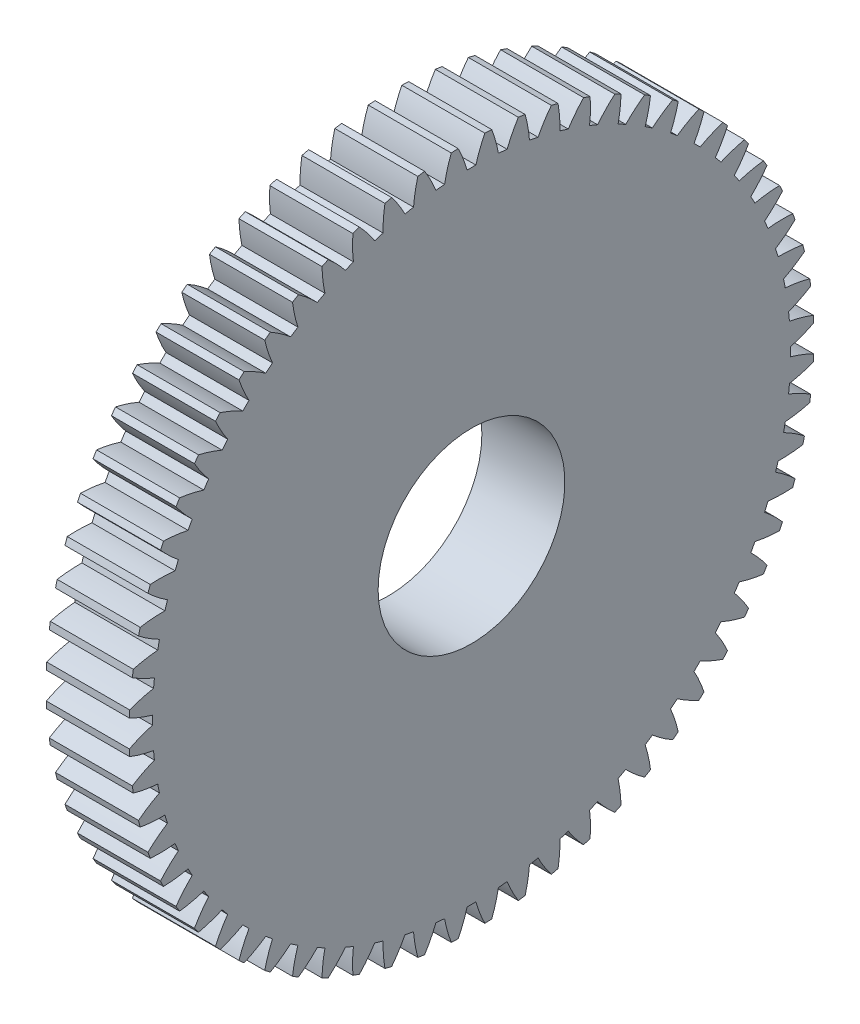
SolidWorks part; units mm, degrees
ref_plane "Plane1" through (0, 0, 0) normal (0, 0, 1) x (1, 0, 0)
ref_plane "Plane2" through (0, 0, 0) normal (0, 1, 0) x (1, 0, 0)
ref_plane "Plane3" through (0, 0, 0) normal (1, 0, 0) x (0, 0, -1)
sketch "HoldingSke" plane through (0, 0, 0) normal (0, 1, 0) x (1, 0, 0)
  line L0 (0, 0) -> (0.0877, -0.1798)
  line L1 (-15, 0) -> (100, 0) construction
  line L2 (0, 0) -> (-2.1039, 2.3779)
  line L3 (0, 0) -> (-11.863, 4.5341)
  line L4 (0, 0) -> (3.7858, 7.762)
  line L5 (0, 0) -> (-46.8476, -17.4728)
  line L6 (0, 0) -> (-33.1585, -22.3721)
  line L7 (-2.1039, 2.3779) -> (8.6586, 51.2059)
  line L8 (-76.2, 54.61) -> (-72.9, 54.61)
  line L9 (-71.009, 38.7566) -> (-53.1078, 45.2721)
  line L10 (-76.2, 71.12) -> (104.1128, 71.12)
  line L11 (0, 0) -> (-40, 0)
  line L12 (-76.2, 101.6) -> (-76.033, 101.6)
  line L13 (24.9733, 27.94) -> (52.9518, 28.4284)
  line L14 (24.9733, 27.94) -> (24.9743, 27.94)
  line L15 (24.9733, 27.94) -> (100.4006, 29.5858)
  line L16 (-63.627, -5) -> (-12.827, -5)
  circle A0 centre (0, 0) radius 20
  circle A1 centre (0, 0) radius 37.5
  circle A2 centre (0, 0) radius 37.5
  circle A3 centre (0, 0) radius 20
  dimension "MHD" = 75
  dimension "Hub_dia" = 75
  dimension "Bore" = 40
  dimension "MBD" = 40
  dimension "Num_teeth" = 64
  dimension "Pitch" = 0.2
  dimension "Overall_len" = 50
  dimension "Show_teeth" = 64
  dimension "Thickness" = 40
  dimension "OAL" = 50.0001
  dimension "T_dim" = 3.3
  dimension "Ap" = 20
  dimension "H" = 19.05
  dimension "Pitch_radius" = 180.3128
  dimension "Width" = 40
  dimension "Backlash" = 0.167
  dimension "Addendum_fac" = 1
  dimension "Dedendum_fac" = 1.25
  dimension "Clearance_fac" = 0.25
  dimension "Dedendum_add" = 0.001
  dimension "Module" = 5
sketch "BasProSke" plane through (0, 0, 0) normal (0, 1, 0) x (1, 0, 0)
  line L0 (-10, 0) -> (60, 0) construction
  line L1 (0, 0) -> (0, 165)
  line L2 (0, 0) -> (40, 0)
  line L3 (40, 0) -> (40, 165)
  line L4 (40, 165) -> (0, 165)
  dimension "Thickness" = 40
  dimension "Diameter" = 330
revolve "Base-Revolve" add sketch "BasProSke" angle 360 about L0
sketch "TooCutSke" plane through (0, 0, 0) normal (1, 0, 0) x (0, 0, -1)
  line L1 (0, 0) -> (0, 107) construction
  line L2 (0, 0) -> (-4.2188, 159.9444) construction
  line L3 (0, 0) -> (-15.6976, 319.5321) construction
  line L4 (-4.2188, 159.9444) -> (-7.8488, 159.766) construction
  arc A0 (2.1013, 153.7346) -> (-2.1013, 153.7346) centre (0, 0) ccw
  arc A1 (6.4457, 164.8995) -> (-6.4457, 164.8995) centre (0, 0) ccw
  circle A2 centre (0, 0) radius 160 construction
  circle A3 centre (0, 0) radius 150.3508 construction
  arc A4 (-2.1013, 153.7346) -> (-6.4457, 164.8995) centre (-63.6555, 136.2107) ccw
  arc A5 (6.4457, 164.8995) -> (2.1013, 153.7346) centre (63.6555, 136.2107) ccw
  dimension "Root_dia" = 307.498
  dimension "Overcut_dia" = 330.0508
  dimension "Pitch_dia" = 320
  dimension "Base_dia" = 300.7016
  dimension "Flank_rad" = 64
  dimension "Half_ang" = 2.813
  dimension "Half_CT" = 3.6343
extrude "ToothCut" cut sketch "TooCutSke" along normal through all
fillet "Breaks" [suppressed] radius 0.1
fillet "RootFillets" [suppressed] radius 1.251
pattern_circular "TeethCuts" count 64 over 360 about axis through (0, 0, 0) along (1, 0, 0) of "ToothCut", "RootFillets", "Breaks"
sketch "HubNeaOneSke" plane through (0, 0, 0) normal (-1, 0, 0) x (0, 0, 1)
  circle A0 centre (0, 0) radius 37.5
  dimension "Diameter" = 75
extrude "HubNearOne" [suppressed] add sketch "HubNeaOneSke" along normal blind 10.0001
sketch "HubNeaBotSke" plane through (0, 0, 0) normal (-1, 0, 0) x (0, 0, 1)
  circle A0 centre (0, 0) radius 37.5
  dimension "Diameter" = 75
extrude "HubNearBoth" [suppressed] add sketch "HubNeaBotSke" along normal blind 5
ref_plane "FarPln" through (40, 0, 0) normal (1, 0, 0) x (0, 0, -1)
sketch "HubFarSke" plane through (40, 0, 0) normal (1, 0, 0) x (0, 0, -1)
  circle A0 centre (0, 0) radius 37.5
  dimension "Diameter" = 75
extrude "HubFar" [suppressed] add sketch "HubFarSke" along normal blind 5
sketch "BorSke" plane through (0, 0, 0) normal (1, 0, 0) x (0, 0, -1)
  circle A0 centre (0, 0) radius 45
  dimension "Diameter" = 90
extrude "Bore" cut sketch "BorSke" along normal mid plane 100.0001
sketch "KeySke" plane through (0, 0, 0) normal (1, 0, 0) x (0, 0, -1)
  line L0 (-6, 0) -> (-6, 23.3)
  line L1 (-6, 23.3) -> (6, 23.3)
  line L2 (6, 23.3) -> (6, 0)
  line L3 (0, 0) -> (0, 34) construction
  line L4 (-6, 0) -> (6, 0)
  dimension "Offset" = 23.3
  dimension "Width" = 12
extrude "Keyway" [suppressed] cut sketch "KeySke" along normal mid plane 100.0001
pattern_circular "Keyway2" [suppressed] count 2 every 90 about axis through (-10, 0, 0) along (1, 0, 0)
equation "' \"Module@HoldingSke\" = 6.35"
equation "' \"Num_teeth@HoldingSke\" = 12"
equation "' \"Ap@HoldingSke\" =  20"
equation "' \"Ap@HoldingSke\" = 20"
equation "' \"Width@HoldingSke\" = 0.5 * 25.4"
equation "' \"Hub_dia@HoldingSke\"= 1 * 25.4"
equation "' \"Hub_dia@HoldingSke\" = 1 * 25.4"
equation "' \"Overall_len@HoldingSke\" = 1.0 * 25.4"
equation "' \"Bore@HoldingSke\" = 0.75 * 25.4"
equation "' \"T_dim@HoldingSke\" = 0.1 * 25.4"
equation "' \"Width@KeySke\" = 0.25 * 25.4"
equation "' \"Show_teeth@HoldingSke\" = 13"
equation "' \"Backlash@HoldingSke\" = 0.009 * 25.4"
equation "' \"Addendum_fac@HoldingSke\" = 1.0"
equation "' \"Dedendum_fac@HoldingSke\" = 1.25"
equation "' \"Dedendum_add@HoldingSke\" = 0.00005 * 25.4"
equation "' \"Clearance_fac@HoldingSke\" = 0.25"
equation "\"Pitch@HoldingSke\" = 1 / \"Module@HoldingSke\""
equation "\"Overcut_dia@TooCutSke\" = (\"Num_teeth@HoldingSke\" + 2 * \"Addendum_fac@HoldingSke\") / \"Pitch@HoldingSke\" + 0.002 * 25.4"
equation "\"Pitch_dia@TooCutSke\" = \"Num_teeth@HoldingSke\" / \"Pitch@HoldingSke\""
equation "\"Base_dia@TooCutSke\" = \"Num_teeth@HoldingSke\" / \"Pitch@HoldingSke\" * cos((\"Ap@HoldingSke\"  * 3.14159265 / 180))"
equation "\"Root_dia@TooCutSke\" = (\"Num_teeth@HoldingSke\" + 2) / \"Pitch@HoldingSke\" - 2 * (\"Addendum_fac@HoldingSke\" + \"Dedendum_fac@HoldingSke\") / \"Pitch@HoldingSke\" - \"Dedendum_add@HoldingSke\" * 2"
equation "\"Half_ang@TooCutSke\" = 180 / \"Num_teeth@HoldingSke\""
equation "\"Half_CT@TooCutSke\" = \"Num_teeth@HoldingSke\" / \"Pitch@HoldingSke\" * sin((3.14159265 / 2 / \"Num_teeth@HoldingSke\")) / 2 - 7 * \"Backlash@HoldingSke\" / 4"
equation "\"Flank_rad@TooCutSke\" = \"Num_teeth@HoldingSke\" / \"Pitch@HoldingSke\" / 5"
equation "\"Radius@RootFillets\" = \"Clearance_fac@HoldingSke\" / \"Pitch@HoldingSke\" + \"Dedendum_add@HoldingSke\""
equation "\"Break_rad@Breaks\" = 0.02 / \"Pitch@HoldingSke\""
equation "\"Thickness@HoldingSke\" = \"Width@HoldingSke\""
equation "\"OAL@HoldingSke\" = \"Thickness@HoldingSke\""
equation "\"MHD@HoldingSke\" = (\"Num_teeth@HoldingSke\" + 2) / \"Pitch@HoldingSke\" - 2 * (\"Addendum_fac@HoldingSke\" + \"Dedendum_fac@HoldingSke\")  / \"Pitch@HoldingSke\" - \"Dedendum_add@HoldingSke\" * 2"
equation "\"MBD@HoldingSke\" = (\"Num_teeth@HoldingSke\" + 2) / \"Pitch@HoldingSke\" - 2 * (\"Addendum_fac@HoldingSke\" + \"Dedendum_fac@HoldingSke\")  / \"Pitch@HoldingSke\" - \"Dedendum_add@HoldingSke\" * 2 - 0.002 * 25.4"
equation "\"MHD@HoldingSke\" = ((sgn( \"MHD@HoldingSke\" - \"Hub_dia@HoldingSke\" )-1)*( \"MHD@HoldingSke\" - \"Hub_dia@HoldingSke\" ))/-2+ \"Hub_dia@HoldingSke\""
equation "\"MBD@HoldingSke\" = ((sgn( \"MBD@HoldingSke\" - \"Bore@HoldingSke\" )-1)*( \"MBD@HoldingSke\" - \"Bore@HoldingSke\" ))/-2+ \"Bore@HoldingSke\""
equation "\"OAL@HoldingSke\" = ((sgn( \"OAL@HoldingSke\" - \"Overall_len@HoldingSke\" )+1)*( \"OAL@HoldingSke\" - \"Overall_len@HoldingSke\" ))/2 + \"Overall_len@HoldingSke\" + 0.000002 * 25.4"
equation "\"Num_teeth@TeethCuts\" = int( \"Show_teeth@HoldingSke\" ) + 1"
equation "\"Num_teeth@TeethCuts\" = ((sgn( \"Num_teeth@TeethCuts\" - \"Num_teeth@HoldingSke\" )-1)*( \"Num_teeth@TeethCuts\" - \"Num_teeth@HoldingSke\" ))/-2+ \"Num_teeth@HoldingSke\""
equation "\"Num_teeth@TeethCuts\" = ((sgn( \"Num_teeth@TeethCuts\" - 2.0)+1)*( \"Num_teeth@TeethCuts\" - 2.0))/2 +2.0"
equation "\"Angle@TeethCuts\" = 360.0 / \"Num_teeth@HoldingSke\""
equation "\"Diameter@BasProSke\" = (\"Num_teeth@HoldingSke\" + 2 * \"Addendum_fac@HoldingSke\") / \"Pitch@HoldingSke\""
equation "\"Thickness@BasProSke\"  = \"Thickness@HoldingSke\""
equation "' \"Fillet_rad@BasProSke\" =  \"Thickness@HoldingSke\" * 0.05"
equation "' \"Fillet_rad@BasProSke\" = \"Thickness@HoldingSke\" * 0.05"
equation "\"MHD@HoldingSke\" = ((sgn( \"MHD@HoldingSke\" - \"Root_dia@TooCutSke\" )-1)*( \"MHD@HoldingSke\" - \"Root_dia@TooCutSke\" ))/-2+ \"Root_dia@TooCutSke\""
equation "\"Diameter@HubNeaOneSke\" = \"MHD@HoldingSke\""
equation "\"Length@HubNearOne\" = \"OAL@HoldingSke\" - \"Thickness@BasProSke\""
equation "\"Diameter@HubNeaBotSke\" = \"MHD@HoldingSke\""
equation "\"Length@HubNearBoth\" = ( \"OAL@HoldingSke\" - \"Thickness@BasProSke\" ) / 2.0"
equation "\"Thickness@FarPln\" = \"Thickness@BasProSke\""
equation "\"Diameter@HubFarSke\" = \"MHD@HoldingSke\""
equation "\"Length@HubFar\" = ( \"OAL@HoldingSke\" - \"Thickness@BasProSke\" ) / 2.0"
equation "\"Diameter@BorSke\"=\"MBD@HoldingSke\"+50mm"
equation "\"D1@Bore\" = \"OAL@HoldingSke\" * 2.0"
equation "\"D1@Keyway\" = \"OAL@HoldingSke\" * 2.0"
equation "\"Offset@KeySke\" = \"T_dim@HoldingSke\" + \"MBD@HoldingSke\" / 2.0"
